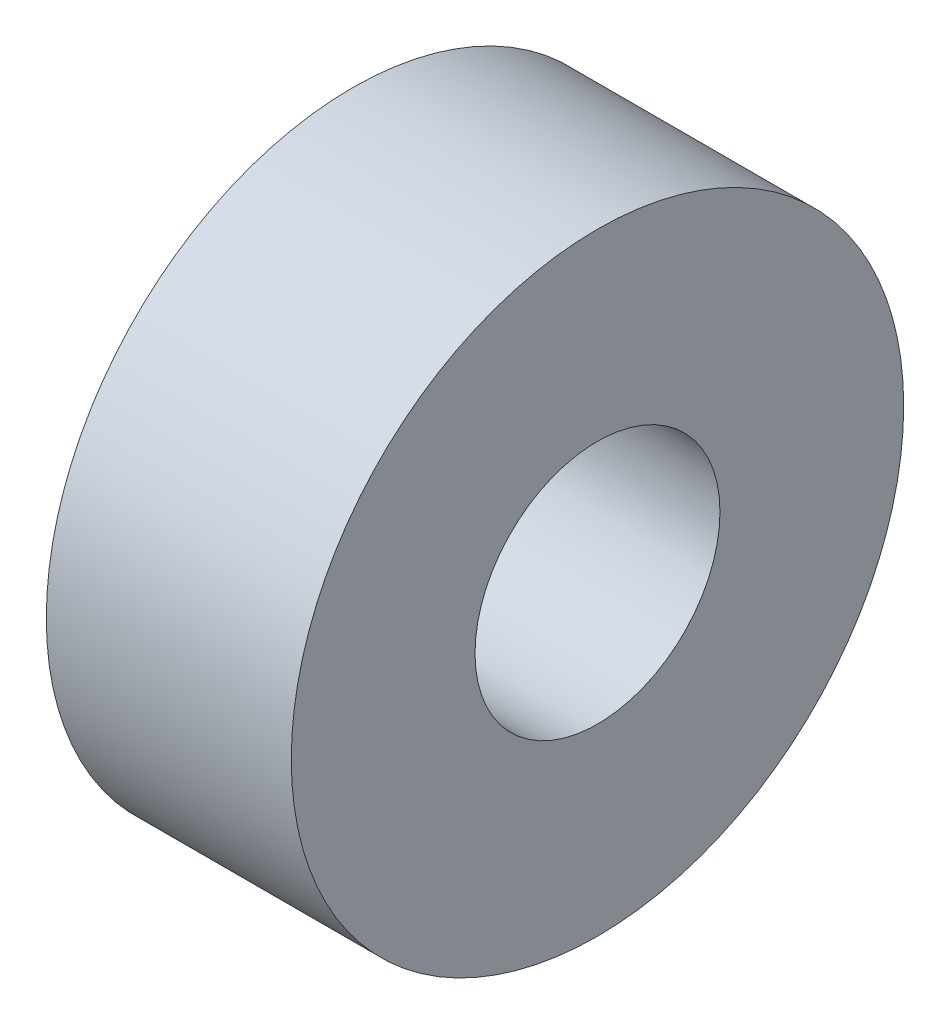
SolidWorks part; units mm, degrees
ref_plane "Front Plane" through (0, 0, 0) normal (0, 0, 1) x (1, 0, 0)
ref_plane "Top Plane" through (0, 0, 0) normal (0, 1, 0) x (1, 0, 0)
ref_plane "Right Plane" through (0, 0, 0) normal (1, 0, 0) x (0, 0, -1)
sketch "Sketch1" plane through (0, 0, 0) normal (1, 0, 0) x (0, 0, -1)
  circle A0 centre (0, 0) radius 15.875
  circle A1 centre (0, 0) radius 6.35
  dimension "D1" = 31.75
  dimension "D2" = 12.7
extrude "Boss-Extrude1" add sketch "Sketch1" along normal blind 12.7
